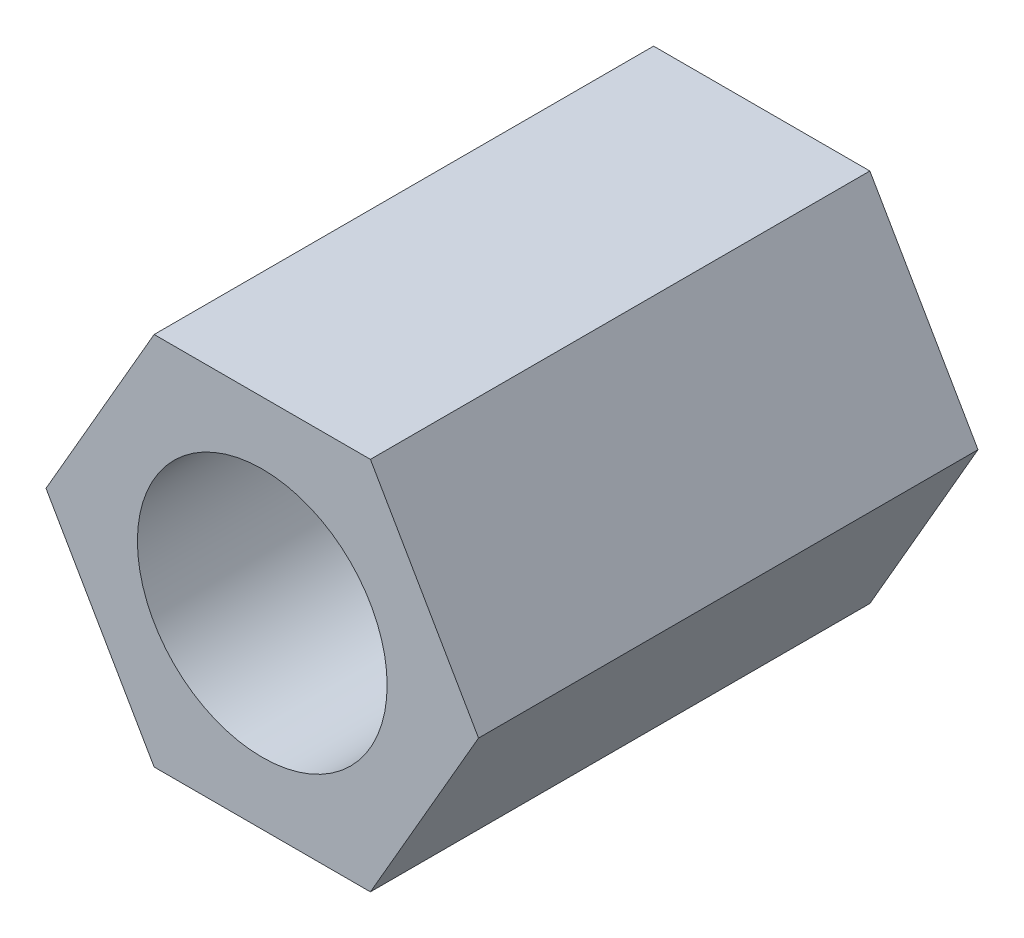
SolidWorks part; units mm, degrees
material "铸造不锈钢"
ref_plane "前视基准面" through (0, 0, 0) normal (0, 0, 1) x (1, 0, 0)
ref_plane "上视基准面" through (0, 0, 0) normal (0, 1, 0) x (1, 0, 0)
ref_plane "右视基准面" through (0, 0, 0) normal (1, 0, 0) x (0, 0, -1)
other "Configuration Table"
sketch "草图1" plane through (0, 0, 0) normal (0, 0, 1) x (1, 0, 0)
  line L1 (3.4641, 0) -> (1.7321, 3)
  line L2 (1.7321, 3) -> (-1.7321, 3)
  line L3 (-1.7321, 3) -> (-3.4641, 0)
  line L4 (-3.4641, 0) -> (-1.7321, -3)
  line L5 (-1.7321, -3) -> (1.7321, -3)
  line L6 (1.7321, -3) -> (3.4641, 0)
  circle A0 centre (0, 0) radius 3 construction
  circle A1 centre (0, 0) radius 2
  dimension "D2" = 4
  dimension "D1" = 6
extrude "凸台-拉伸1" add sketch "草图1" along normal blind 8
